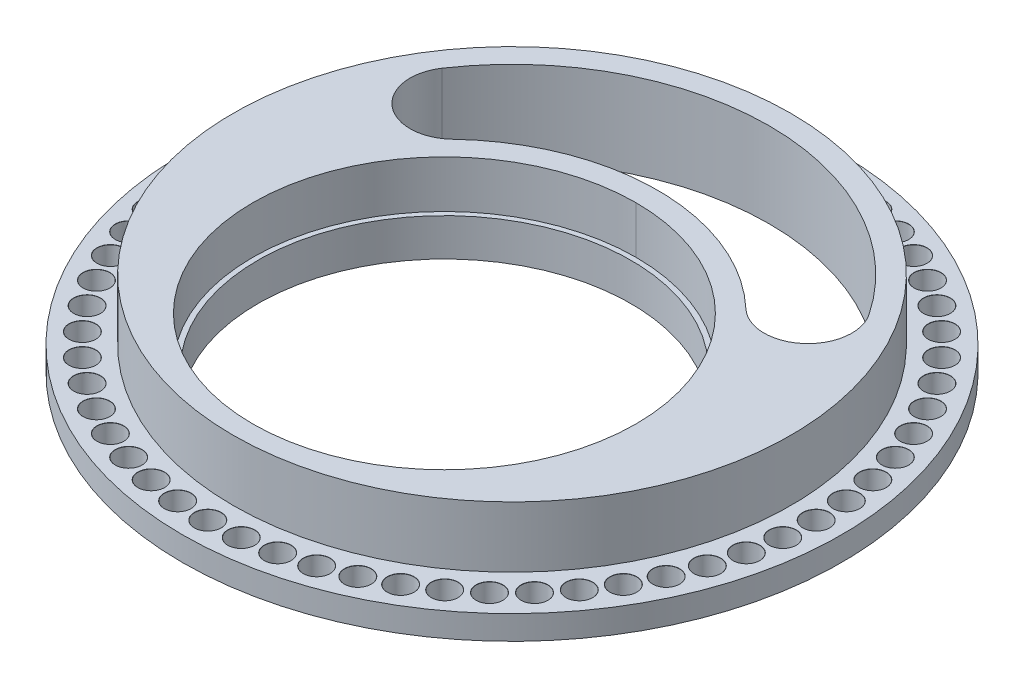
SolidWorks part; units mm, degrees
material "7075-T6, Plate (SS)"
ref_plane "X-Y Datum" through (0, 0, 0) normal (0, 0, 1) x (1, 0, 0)
ref_plane "X-Z Datum" through (0, 0, 0) normal (0, 1, 0) x (1, 0, 0)
ref_plane "Y-Z Datum" through (0, 0, 0) normal (1, 0, 0) x (0, 0, -1)
sketch "Sketch1" plane through (0, 0, 0) normal (0, 1, 0) x (1, 0, 0)
  line L0 (0, 0) -> (0, -12.7) construction
  line L1 (0, -43.0151) -> (0, 43.0151) construction
  line L2 (0, 61.9125) -> (0, 52.3875)
  circle A0 centre (0, -12.7) radius 35.052
  circle A1 centre (0, 0) radius 52.3875 construction
  circle A2 centre (0, 0) radius 57.15 construction
  circle A3 centre (0, 0) radius 61.9125
  point P12 (0, 57.15)
  dimension "D2" = 70.104
  dimension "D3" = 104.775
  dimension "D4" = 123.825
  dimension "D5" = 114.3
  dimension "D1" = 12.7
extrude "Boss-Extrude1" add sketch "Sketch1" along normal blind 4.5212
sketch "Sketch3" plane through (0, 4.5212, 0) normal (0, 1, 0) x (1, 0, 0)
  circle A0 centre (0, 0) radius 52.3875 construction
  circle A1 centre (0, 0) radius 52.3875
extrude "Boss-Extrude2" add sketch "Sketch3" along normal blind 11.43
sketch "Sketch4" plane through (0, 0, 0) normal (0, -1, 0) x (1, 0, 0)
  circle A0 centre (0, 12.7) radius 35.052 construction
  circle A1 centre (0, 12.7) radius 35.052
extrude "Cut-Extrude1" cut sketch "Sketch4" against normal through all
sketch "Sketch9" plane through (0, 15.9512, 0) normal (0, 1, 0) x (1, 0, 0)
  circle A0 centre (0, -12.7) radius 35.052 construction
  circle A1 centre (0, -12.7) radius 35.052 construction
  circle A2 centre (0, -12.7) radius 36
  dimension "D1" = 72
extrude "Cut-Extrude3" cut sketch "Sketch9" against normal blind 8.89
hole_wizard "Ø5.0mm Dowel Hole1" positions "Sketch7" profile "Sketch8" hole size "Ø5.0" standard "ANSI Metric" end condition through all
sketch "Sketch7" plane through (0, 4.5212, 0) normal (0, 1, 0) x (1, 0, 0)
  point P0 (0, 57.15)
sketch "Sketch8" plane through (0, 4.5212, -57.15) normal (1, 0, 0) x (0, 0, 1)
  line L0 (0, 0) -> (0, 4.5212)
  line L1 (0, 4.5212) -> (2.5, 4.5212)
  line L2 (2.5, 4.5212) -> (2.5, 0.025)
  line L3 (2.5, 0.025) -> (2.525, 0)
  line L5 (2.525, 0) -> (0, 0)
  line L6 (-2.5, 0.025) -> (-2.525, 0) construction
  line L11 (0, -6.35) -> (0, 107.95) construction
  dimension "Thru Hole Dia." = 5
  dimension "Thru Hole Depth" = 4.5212
  dimension "Near C'Sink Dia." = 5.05
  dimension "Near C'Sink Angle" = 90
pattern_circular "CirPattern1" count 60 over 360 about axis through (0, 0, 0) along (0, 1, 0) of "Ø5.0mm Dowel Hole1"
ref_point "Point1"
ref_plane "Plane1" through (0, 0, 0) normal (1, 0, 0) x (0, 0, -1)
split line "Split Line1"
sketch "Sketch10" plane through (0, 15.9512, 0) normal (0, 1, 0) x (1, 0, 0)
  circle A0 centre (0, 0) radius 52.3875 construction
  circle A1 centre (0, 0) radius 52.3875 construction
  circle A3 centre (-33.2491, 22.3603) radius 8.255 construction
  circle A4 centre (33.2491, 22.3603) radius 8.255 construction
  arc A7 (0, -52.764) -> (0, 27.364) centre (0, -12.7) ccw
  arc A8 (0, 27.364) -> (0, -52.764) centre (0, -12.7) ccw
  arc A9 (0, -52.764) -> (0, 27.364) centre (0, -12.7) ccw construction
  arc A10 (0, 27.364) -> (0, -52.764) centre (0, -12.7) ccw construction
  circle A29 centre (0, 0) radius 48.3235 construction
  arc A30 (-27.5687, 16.3704) -> (27.5687, 16.3704) centre (0, -12.7) cw
  arc A31 (-40.0992, 26.967) -> (40.0992, 26.967) centre (0, 0) cw
  arc A32 (-40.0992, 26.967) -> (-27.5687, 16.3704) centre (-33.2491, 22.3603) ccw
  arc A33 (27.5687, 16.3704) -> (40.0992, 26.967) centre (33.2491, 22.3603) ccw
  dimension "D3" = 16.51
  dimension "D1" = 4.064
  dimension "D2" = 4.064
extrude "Cut-Extrude5" cut sketch "Sketch10" against normal through all contours A33 A31 A32 A30
